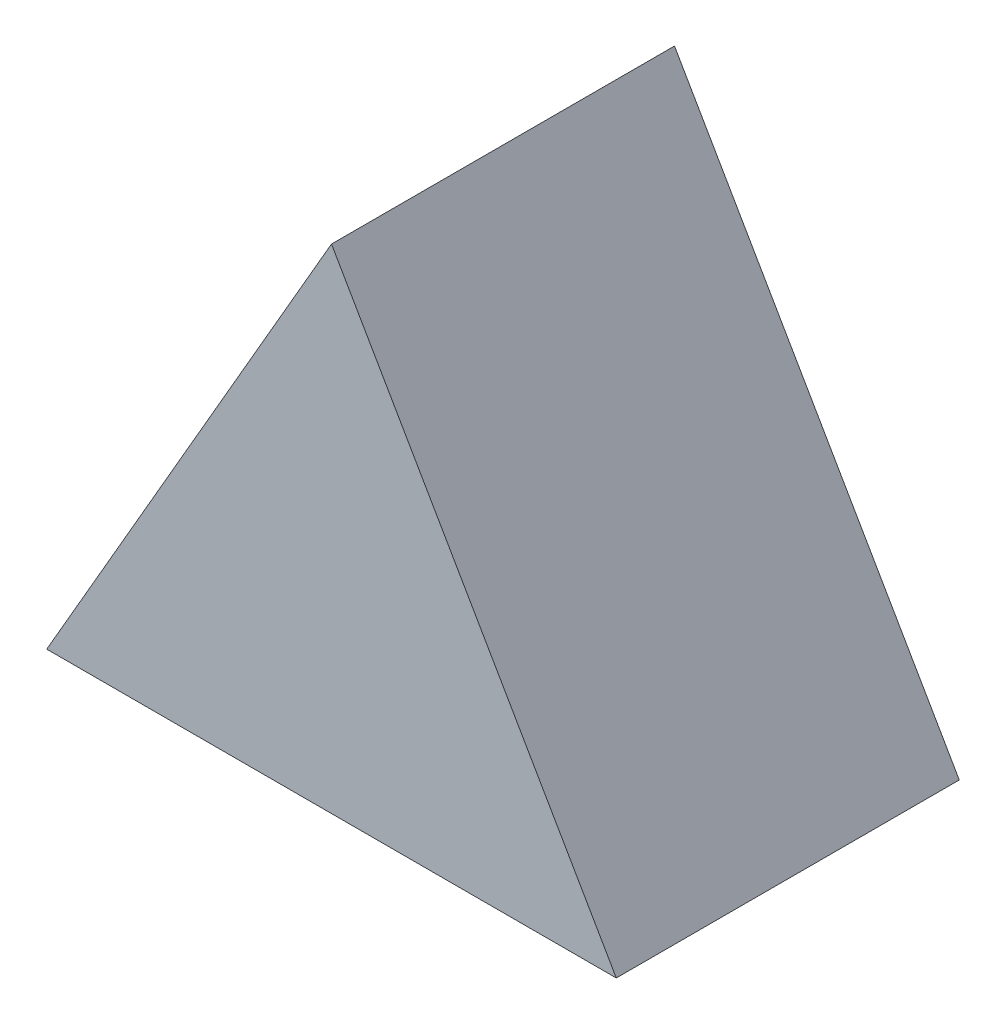
SolidWorks part; units mm, degrees
ref_plane "Спереди" through (0, 0, 0) normal (0, 0, 1) x (1, 0, 0)
ref_plane "Сверху" through (0, 0, 0) normal (0, 1, 0) x (1, 0, 0)
ref_plane "Справа" through (0, 0, 0) normal (1, 0, 0) x (0, 0, -1)
sketch "Эскиз1" plane through (0, 0, 0) normal (0, 0, 1) x (1, 0, 0)
  line L0 (-0.3091, 3.4646) -> (-3.4641, -2)
  line L1 (-3.4641, -2) -> (2.8459, -2)
  line L2 (2.8459, -2) -> (-0.3091, 3.4646)
  dimension "D1" = 6.31
  dimension "D2" = 6.31
  dimension "D3" = 6.31
  dimension "D4" = 2
  dimension "D5" = 2
extrude "Бобышка-Вытянуть1" add sketch "Эскиз1" along normal blind 3.8
